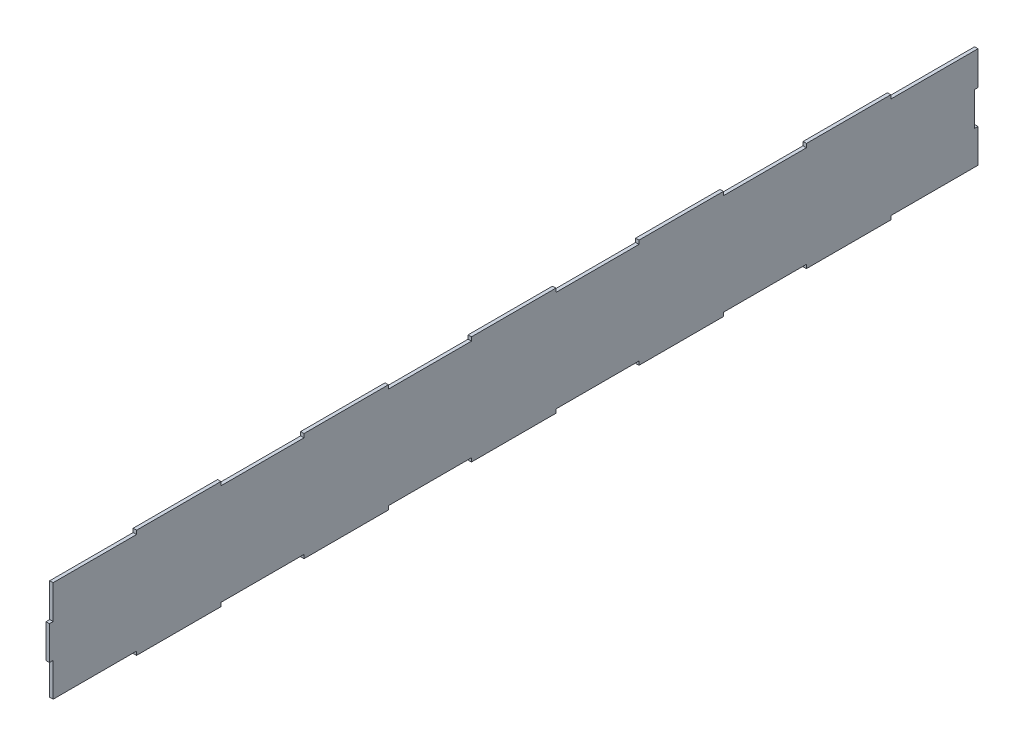
SolidWorks part; units mm, degrees
ref_plane "Front Plane" through (0, 0, 0) normal (0, 0, 1) x (1, 0, 0)
ref_plane "Top Plane" through (0, 0, 0) normal (0, 1, 0) x (1, 0, 0)
ref_plane "Right Plane" through (0, 0, 0) normal (1, 0, 0) x (0, 0, -1)
sketch "Sketch1" plane through (0, 0, 0) normal (1, 0, 0) x (0, 0, -1)
  line L0 (-216.6667, 23.75) -> (-177.4327, 23.75)
  line L1 (-177.4327, 23.75) -> (-177.4327, 25.51)
  line L2 (-216.6667, 23.75) -> (-216.6667, 7.9167)
  line L3 (-216.6667, 0) -> (216.6667, 0)
  line L4 (216.6667, 7.9167) -> (216.6667, 0)
  line L5 (-177.4327, 25.51) -> (-137.7188, 25.51)
  line L6 (-137.7188, 25.51) -> (-137.7188, 23.75)
  line L7 (-137.7188, 23.75) -> (-98.6448, 23.75)
  line L8 (-98.6448, 23.75) -> (-98.6448, 25.51)
  line L9 (-98.6448, 25.51) -> (-58.9309, 25.51)
  line L10 (-58.9309, 25.51) -> (-58.9309, 23.75)
  line L11 (-58.9309, 23.75) -> (-19.857, 23.75)
  line L12 (-19.857, 23.75) -> (-19.857, 25.51)
  line L13 (-19.857, 25.51) -> (19.857, 25.51)
  line L14 (19.857, 25.51) -> (19.857, 23.75)
  line L15 (19.857, 23.75) -> (58.9309, 23.75)
  line L16 (58.9309, 23.75) -> (58.9309, 25.51)
  line L17 (58.9309, 25.51) -> (98.6448, 25.51)
  line L18 (98.6448, 25.51) -> (98.6448, 23.75)
  line L19 (98.6448, 23.75) -> (137.7188, 23.75)
  line L20 (137.7188, 23.75) -> (137.7188, 25.51)
  line L21 (137.7188, 25.51) -> (177.4327, 25.51)
  line L22 (177.4327, 25.51) -> (177.4327, 23.75)
  line L23 (-216.6667, 0) -> (-218.4267, 0)
  line L24 (177.4327, 23.75) -> (216.6667, 23.75)
  line L29 (-216.6667, 7.9167) -> (-218.4267, 7.9167)
  line L30 (-218.4267, 0) -> (-218.4267, 7.9167)
  line L31 (216.6667, 23.75) -> (218.4267, 23.75)
  line L33 (216.6667, 7.9167) -> (218.4267, 7.9167)
  line L34 (218.4267, 23.75) -> (218.4267, 7.9167)
  dimension "D1" = 23.75
  dimension "D2" = 433.3333
  dimension "D4" = 7.9167
  dimension "D3" = 1.76
  dimension "D5" = 39.2339
  dimension "D6" = 39.7139
  dimension "D7" = 39.0739
extrude "Up" add sketch "Sketch1" along normal blind 1.6
mirror "Mirror2" about plane through (1.6, 0, 216.6667) normal (0, 1, 0) of "Up"
equation "\"thinkness\"= \"epaisseur\""
equation "\"D3@Sketch1\"= \"thinkness\" + \"jeu\""
equation "\"D1@Up\"= \"thinkness\""
equation "\"D4@Sketch1\"= \"hauteur\" / 6"
equation "\"D1@Up\" = \"thinkness\""
equation "\"hauteur\"= 47.5"
equation "\"largeur\"= \"nbCarre\" * \"Coté\""
equation "\"longueur\"= \"nbCarre\" * \"Coté\""
equation "\"D1@Sketch1\" = \"hauteur\" / 2"
equation "\"D2@Sketch1\"= \"longueur\""
equation "\"D5@Sketch1\"= \"longueur\" / 11 - \"jeu\""
equation "\"jeu\"= 0.16"
equation "\"D6@Sketch1\"= \"longueur\" / 11 + \"jeu\" * 2"
equation "\"D7@Sketch1\"= \"longueur\" / 11 - \"jeu\" * 2"
equation "\"Coté\"= 33.333333"
equation "\"nbCarre\"= 13"
equation "\"epaisseur\"= 1.6"
equation "\"rapportEncoche\"= 0.5"
